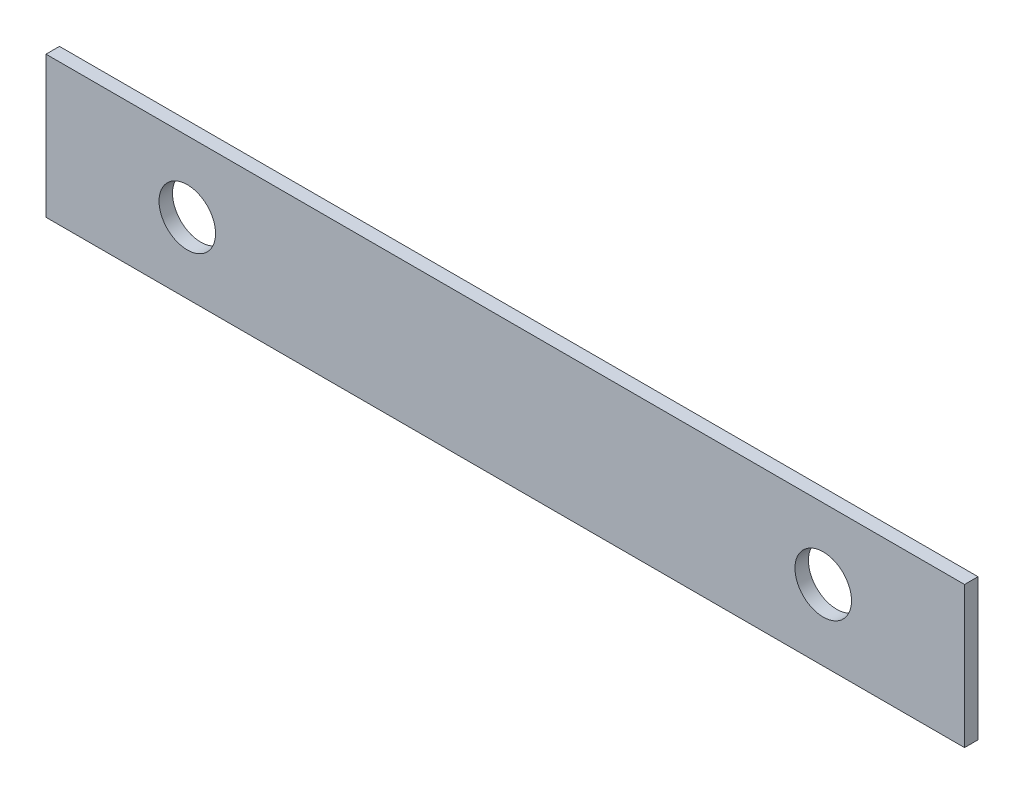
SolidWorks part; units mm, degrees
material "AISI 1020 Acero laminado en frío"
ref_plane "Alzado" through (0, 0, 0) normal (0, 0, 1) x (1, 0, 0)
ref_plane "Planta" through (0, 0, 0) normal (0, 1, 0) x (1, 0, 0)
ref_plane "Vista lateral" through (0, 0, 0) normal (1, 0, 0) x (0, 0, -1)
sketch "Croquis1" plane through (0, 0, 0) normal (0, 0, 1) x (1, 0, 0)
  line L1 (-325, -50) -> (325, -50)
  line L2 (-325, -50) -> (-325, 50)
  line L3 (-325, 50) -> (325, 50)
  line L4 (325, -50) -> (325, 50)
  line L5 (-325, -50) -> (325, 50) construction
  line L6 (-325, 50) -> (325, -50) construction
  point P0 (0, 0)
  dimension "D1" = 650
  dimension "D2" = 100
extrude "Saliente-Extruir1" add sketch "Croquis1" along normal mid plane 9.53
sketch "Croquis3" plane through (0, 0, 4.765) normal (0, 0, 1) x (1, 0, 0)
  line L0 (325, -50) -> (325, 50) construction
  circle A0 centre (225, 0) radius 20
  dimension "D1" = 100
  dimension "D2" = 40
sketch "Croquis4" plane through (0, 0, -4.765) normal (0, 0, -1) x (-1, 0, 0)
  line L0 (325, 50) -> (325, -50) construction
  circle A0 centre (225, 0) radius 20
  point P4 (325, 0)
  dimension "D1" = 100
  dimension "D2" = 40
sketch "Croquis5" plane through (0, 0, -4.765) normal (0, 0, -1) x (-1, 0, 0)
extrude "Cortar-Extruir3" cut sketch "Croquis4" against normal blind 15 contours A0
extrude "Cortar-Extruir4" cut sketch "Croquis3" against normal blind 15 contours A0
